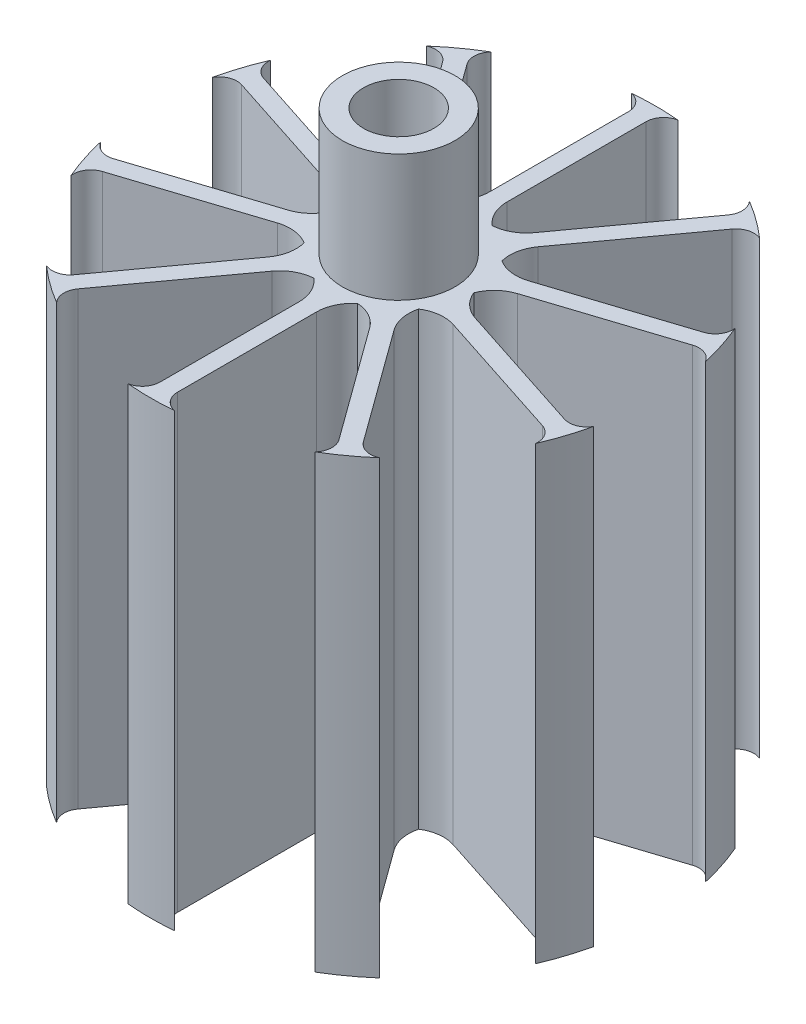
SolidWorks part; units mm, degrees
ref_plane "前视基准面" through (0, 0, 0) normal (0, 0, 1) x (1, 0, 0)
ref_plane "上视基准面" through (0, 0, 0) normal (0, 1, 0) x (1, 0, 0)
ref_plane "右视基准面" through (0, 0, 0) normal (1, 0, 0) x (0, 0, -1)
sketch "草图2" plane through (0, 0, 0) normal (0, 1, 0) x (1, 0, 0)
  line L0 (0, 0.3046) -> (0, 19.0347) construction
  line L1 (-0.6205, 16.9391) -> (-0.6205, 7.0765)
  line L2 (0.6205, 16.9391) -> (0.6205, 7.0765)
  line L3 (9.2755, 14.127) -> (3.4784, 6.1479)
  line L4 (10.2795, 13.3975) -> (4.4824, 5.4184)
  line L5 (15.6286, 6.0351) -> (6.2487, 2.9874)
  line L6 (16.0121, 4.8548) -> (6.6322, 1.8071)
  line L7 (16.0121, -4.2456) -> (6.6322, -1.1978)
  line L8 (15.6286, -5.4259) -> (6.2487, -2.3782)
  line L9 (10.2795, -12.7882) -> (4.4824, -4.8092)
  line L10 (9.2755, -13.5177) -> (3.4784, -5.5387)
  line L11 (0.6205, -16.3299) -> (0.6205, -6.4673)
  line L12 (-0.6205, -16.3299) -> (-0.6205, -6.4673)
  line L13 (-9.2755, -13.5177) -> (-3.4784, -5.5387)
  line L14 (-10.2795, -12.7882) -> (-4.4824, -4.8092)
  line L15 (-15.6286, -5.4259) -> (-6.2487, -2.3782)
  line L16 (-16.0121, -4.2456) -> (-6.6322, -1.1978)
  line L17 (-16.0121, 4.8548) -> (-6.6322, 1.8071)
  line L18 (-15.6286, 6.0351) -> (-6.2487, 2.9874)
  line L19 (-10.2795, 13.3975) -> (-4.4824, 5.4184)
  line L20 (-9.2755, 14.127) -> (-3.4784, 6.1479)
  arc A0 (-17.5073, -3.6572) -> (-16.4924, -6.7808) centre (0, 0.3046) ccw
  arc A2 (-0.6205, 16.9391) -> (-1.6422, 18.1793) centre (-1.8841, 16.9391) ccw
  arc A3 (-0.6205, 7.0765) -> (-1.5542, 5.0878) centre (-3.2054, 7.0765) cw
  arc A4 (0.6205, 7.0765) -> (1.5542, 5.0878) centre (3.2054, 7.0765) ccw
  arc A5 (0.6205, 16.9391) -> (1.6422, 18.1793) centre (1.8841, 16.9391) cw
  arc A6 (4.4824, 5.4184) -> (4.0688, 3.2608) centre (6.5736, 3.8991) ccw
  arc A7 (3.4784, 6.1479) -> (1.5542, 5.0878) centre (1.3872, 7.6672) cw
  arc A8 (10.2795, 13.3975) -> (11.835, 13.8003) centre (11.3018, 12.6547) cw
  arc A9 (9.2755, 14.127) -> (9.178, 15.7308) centre (8.2532, 14.8697) ccw
  arc A10 (6.6322, 1.8071) -> (5.0294, 0.3046) centre (7.4309, -0.6512) ccw
  arc A11 (6.2487, 2.9874) -> (4.0688, 3.2608) centre (5.4499, 5.4457) cw
  arc A12 (16.0121, 4.8548) -> (17.5073, 4.2664) centre (16.4026, 3.653) cw
  arc A13 (15.6286, 6.0351) -> (16.4924, 7.39) centre (15.2381, 7.2369) ccw
  arc A14 (6.2487, -2.3782) -> (4.0688, -2.6516) centre (5.4499, -4.8365) ccw
  arc A15 (6.6322, -1.1978) -> (5.0294, 0.3046) centre (7.4309, 1.2605) cw
  arc A16 (15.6286, -5.4259) -> (16.4924, -6.7808) centre (15.2381, -6.6277) cw
  arc A17 (16.0121, -4.2456) -> (17.5073, -3.6572) centre (16.4026, -3.0438) ccw
  arc A18 (3.4784, -5.5387) -> (1.5542, -4.4786) centre (1.3872, -7.058) ccw
  arc A19 (4.4824, -4.8092) -> (4.0688, -2.6516) centre (6.5736, -3.2899) cw
  arc A20 (9.2755, -13.5177) -> (9.178, -15.1216) centre (8.2532, -14.2604) cw
  arc A21 (10.2795, -12.7882) -> (11.835, -13.1911) centre (11.3018, -12.0455) ccw
  arc A22 (-0.6205, -6.4673) -> (-1.5542, -4.4786) centre (-3.2054, -6.4673) ccw
  arc A23 (0.6205, -6.4673) -> (1.5542, -4.4786) centre (3.2054, -6.4673) cw
  arc A24 (-0.6205, -16.3299) -> (-1.6422, -17.5701) centre (-1.8841, -16.3299) cw
  arc A25 (0.6205, -16.3299) -> (1.6422, -17.5701) centre (1.8841, -16.3299) ccw
  arc A26 (-4.4824, -4.8092) -> (-4.0688, -2.6516) centre (-6.5736, -3.2899) ccw
  arc A27 (-3.4784, -5.5387) -> (-1.5542, -4.4786) centre (-1.3872, -7.058) cw
  arc A28 (-10.2795, -12.7882) -> (-11.835, -13.1911) centre (-11.3018, -12.0455) cw
  arc A29 (-9.2755, -13.5177) -> (-9.178, -15.1216) centre (-8.2532, -14.2604) ccw
  arc A30 (-6.6322, -1.1978) -> (-5.0294, 0.3046) centre (-7.4309, 1.2605) ccw
  arc A31 (-6.2487, -2.3782) -> (-4.0688, -2.6516) centre (-5.4499, -4.8365) cw
  arc A32 (-16.0121, -4.2456) -> (-17.5073, -3.6572) centre (-16.4026, -3.0438) cw
  arc A33 (-15.6286, -5.4259) -> (-16.4924, -6.7808) centre (-15.2381, -6.6277) ccw
  arc A34 (-6.2487, 2.9874) -> (-4.0688, 3.2608) centre (-5.4499, 5.4457) ccw
  arc A35 (-6.6322, 1.8071) -> (-5.0294, 0.3046) centre (-7.4309, -0.6512) cw
  arc A36 (-15.6286, 6.0351) -> (-16.4924, 7.39) centre (-15.2381, 7.2369) cw
  arc A37 (-16.0121, 4.8548) -> (-17.5073, 4.2664) centre (-16.4026, 3.653) ccw
  arc A38 (-3.4784, 6.1479) -> (-1.5542, 5.0878) centre (-1.3872, 7.6672) ccw
  arc A39 (-4.4824, 5.4184) -> (-4.0688, 3.2608) centre (-6.5736, 3.8991) cw
  arc A40 (-9.2755, 14.127) -> (-9.178, 15.7308) centre (-8.2532, 14.8697) cw
  arc A41 (-10.2795, 13.3975) -> (-11.835, 13.8003) centre (-11.3018, 12.6547) ccw
  arc A42 (-16.4924, 7.39) -> (-17.5073, 4.2664) centre (0, 0.3046) ccw
  arc A43 (-9.178, 15.7308) -> (-11.835, 13.8003) centre (0, 0.3046) ccw
  arc A44 (1.6422, 18.1793) -> (-1.6422, 18.1793) centre (0, 0.3046) ccw
  arc A45 (11.835, 13.8003) -> (9.178, 15.7308) centre (0, 0.3046) ccw
  arc A46 (17.5073, 4.2664) -> (16.4924, 7.39) centre (0, 0.3046) ccw
  arc A47 (16.4924, -6.7808) -> (17.5073, -3.6572) centre (0, 0.3046) ccw
  arc A48 (9.178, -15.1216) -> (11.835, -13.1911) centre (0, 0.3046) ccw
  arc A49 (-1.6422, -17.5701) -> (1.6422, -17.5701) centre (0, 0.3046) ccw
  arc A50 (-11.835, -13.1911) -> (-9.178, -15.1216) centre (0, 0.3046) ccw
  point P128 (0, 0.3046)
  dimension "D2" = 35.9
  dimension "D3" = 10
extrude "凸台-拉伸1" add sketch "草图2" along normal blind 32
sketch "草图3" plane through (0, 32, 0) normal (0, 1, 0) x (1, 0, 0)
  circle A0 centre (0, 0) radius 4
  dimension "D1" = 8
extrude "凸台-拉伸2" add sketch "草图3" along normal blind 9
sketch "草图4" plane through (0, 41, 0) normal (0, 1, 0) x (1, 0, 0)
  circle A0 centre (0, 0) radius 2.5
  dimension "D1" = 5
extrude "切除-拉伸1" cut sketch "草图4" against normal through all
